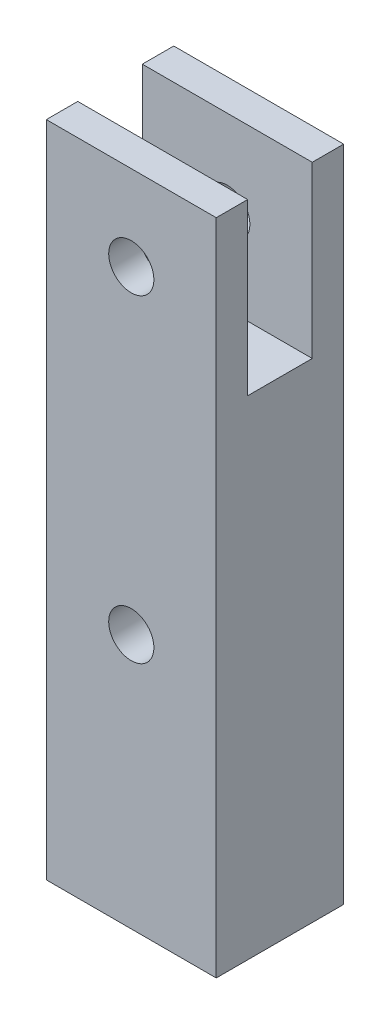
SolidWorks part; units mm, degrees
ref_plane "Front Plane" through (0, 0, 0) normal (0, 0, 1) x (1, 0, 0)
ref_plane "Top Plane" through (0, 0, 0) normal (0, 1, 0) x (1, 0, 0)
ref_plane "Right Plane" through (0, 0, 0) normal (1, 0, 0) x (0, 0, -1)
sketch "Sketch1" plane through (0, 0, 0) normal (0, 0, 1) x (1, 0, 0)
  line L0 (-12.7, 23.8125) -> (-12.7, 36.5125)
  line L1 (-12.7, -61.9125) -> (12.7, -61.9125)
  line L2 (-12.7, -61.9125) -> (-12.7, 23.8125)
  line L3 (-12.7, 23.8125) -> (12.7, 23.8125) construction
  line L4 (12.7, -61.9125) -> (12.7, 23.8125)
  line L5 (143.51, -61.9125) -> (-448.31, -61.9125) construction
  line L6 (88.1063, 23.8125) -> (77.6288, 23.8125) construction
  line L7 (-12.7, 36.5125) -> (12.7, 36.5125)
  line L8 (12.7, 36.5125) -> (12.7, 23.8125)
  arc A0 (12.7, 23.8125) -> (-12.7, 23.8125) centre (0, 23.8125) ccw construction
  circle A1 centre (0, 23.8125) radius 3.3782
  circle A2 centre (0, -23.8125) radius 3.3782
  point P0 (0, 0)
  point P14 (0, -61.9125)
  dimension "D3" = 6.7564
  dimension "D2" = 6.7564
  dimension "D1" = 25.4
  dimension "D4" = 23.8125
  dimension "D5" = 23.8125
extrude "Boss-Extrude1" add sketch "Sketch1" along normal mid plane 19.05
sketch "Sketch3" plane through (12.7, 0, 0) normal (1, 0, 0) x (0, 0, -1)
  line L1 (4.826, 11.1125) -> (-4.826, 11.1125)
  line L2 (4.826, 11.1125) -> (4.826, 36.5125)
  line L3 (4.826, 36.5125) -> (-4.826, 36.5125)
  line L4 (-4.826, 11.1125) -> (-4.826, 36.5125)
  line L5 (4.826, 11.1125) -> (-4.826, 36.5125) construction
  line L6 (4.826, 36.5125) -> (-4.826, 11.1125) construction
  line L7 (-9.525, 36.5125) -> (9.525, 36.5125) construction
  point P0 (0, 23.8125)
  dimension "D1" = 25.4
  dimension "D2" = 9.652
extrude "Cut-Extrude1" cut sketch "Sketch3" against normal through all
equation "\"D5@Sketch1\"=\"D4@Sketch1\""
